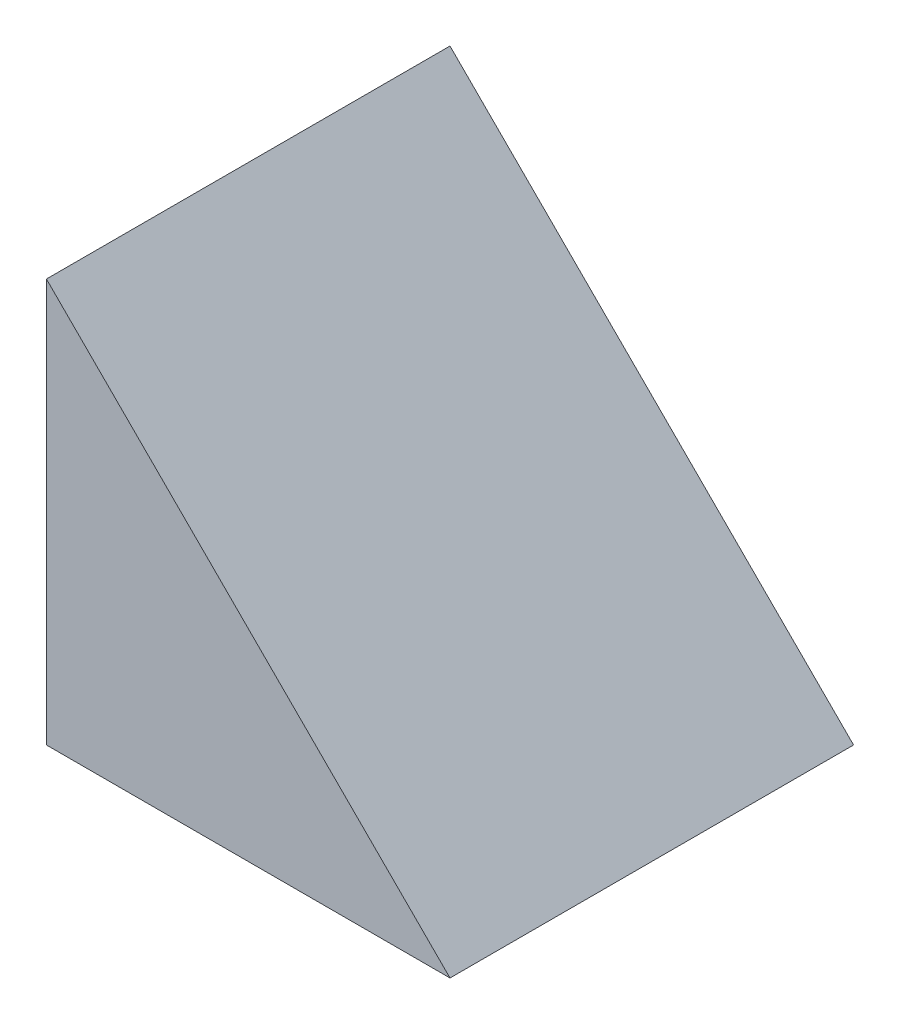
SolidWorks part; units mm, degrees
ref_plane "Front Plane" through (0, 0, 0) normal (0, 0, 1) x (1, 0, 0)
ref_plane "Top Plane" through (0, 0, 0) normal (0, 1, 0) x (1, 0, 0)
ref_plane "Right Plane" through (0, 0, 0) normal (1, 0, 0) x (0, 0, -1)
sketch "Sketch1" plane through (0, 0, 0) normal (0, 0, 1) x (1, 0, 0)
  line L0 (0, 0) -> (0, 30)
  line L1 (0, 30) -> (30, 0)
  line L2 (30, 0) -> (0, 0)
  dimension "D1" = 30
  dimension "D2" = 30
extrude "Boss-Extrude1" add sketch "Sketch1" along normal blind 30
equation "\"D2@Sketch1\"=\"D1@Sketch1\""
equation "\"D1@Boss-Extrude1\"=\"D1@Sketch1\""
